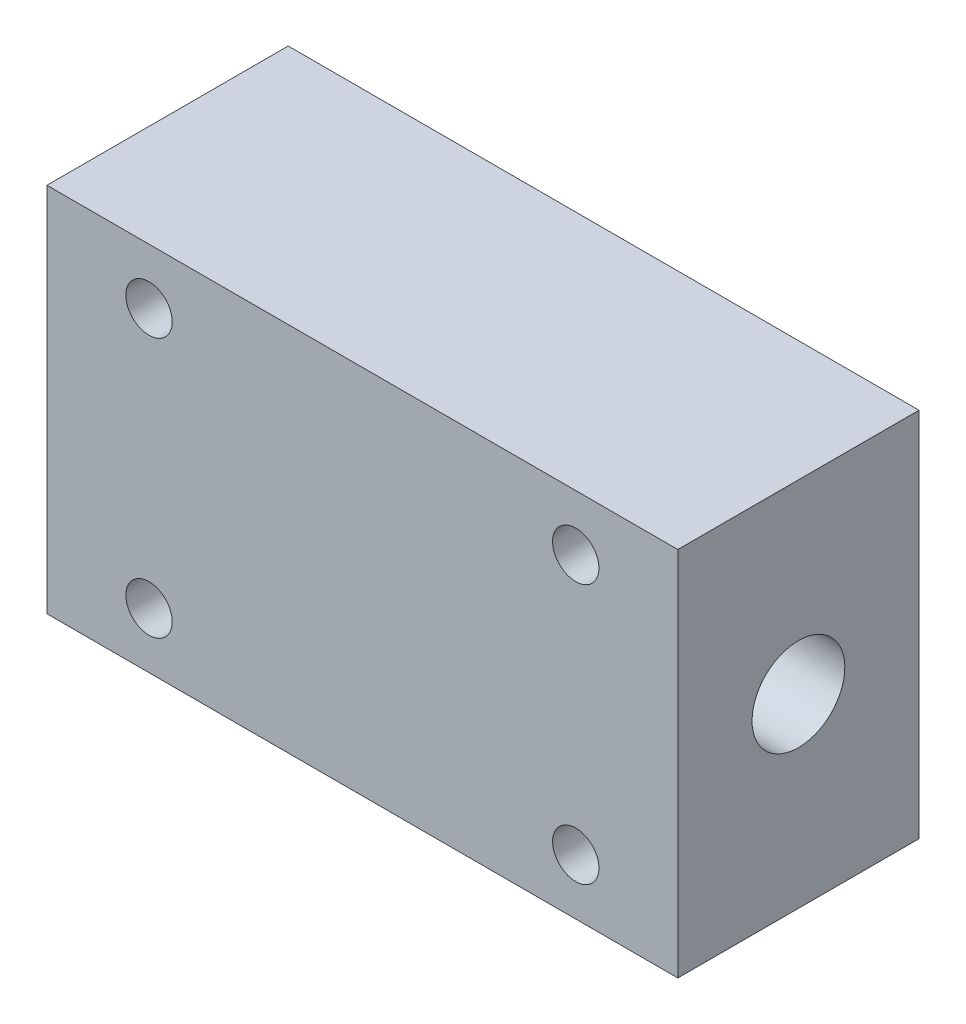
SolidWorks part; units mm, degrees
material "6061-T4 (SS)"
ref_plane "Piano frontale" through (0, 0, 0) normal (0, 0, 1) x (1, 0, 0)
ref_plane "Piano superiore" through (0, 0, 0) normal (0, 1, 0) x (1, 0, 0)
ref_plane "Piano destro" through (0, 0, 0) normal (1, 0, 0) x (0, 0, -1)
sketch "Schizzo1" plane through (0, 0, 0) normal (0, 0, 1) x (1, 0, 0)
  line L1 (0, 0) -> (68, 0)
  line L2 (0, 0) -> (0, 40)
  line L3 (0, 40) -> (68, 40)
  line L4 (68, 0) -> (68, 40)
  dimension "D1" = 68
  dimension "D2" = 40
extrude "Estrusione-Estrusione1" add sketch "Schizzo1" against normal blind 26
sketch "Schizzo2" plane through (0, 0, 0) normal (-1, 0, 0) x (0, 0, 1)
  line L0 (0, 20) -> (-26, 20) construction
  line L1 (0, 40) -> (0, 0) construction
  line L2 (-26, 40) -> (-26, 0) construction
  circle A0 centre (-13, 20) radius 5
  dimension "D2" = 10
  dimension "D1" = 13
extrude "Taglio-Estrusione1" cut sketch "Schizzo2" against normal through all
sketch "Schizzo3" plane through (0, 0, -26) normal (0, 0, -1) x (-1, 0, 0)
  line L0 (0, 20) -> (-68, 20) construction
  line L1 (0, 40) -> (0, 0) construction
  line L2 (-68, 0) -> (-68, 40) construction
  line L3 (-34, 40) -> (-34, 0) construction
  line L4 (-68, 40) -> (0, 40) construction
  line L5 (0, 0) -> (-68, 0) construction
  circle A0 centre (-11, 34) radius 2.5
  circle A1 centre (-57, 34) radius 2.5
  circle A2 centre (-57, 6) radius 2.5
  circle A3 centre (-11, 6) radius 2.5
  dimension "D3" = 5
  dimension "D1" = 14
  dimension "D2" = 23
extrude "Taglio-Estrusione2" cut sketch "Schizzo3" against normal through all
